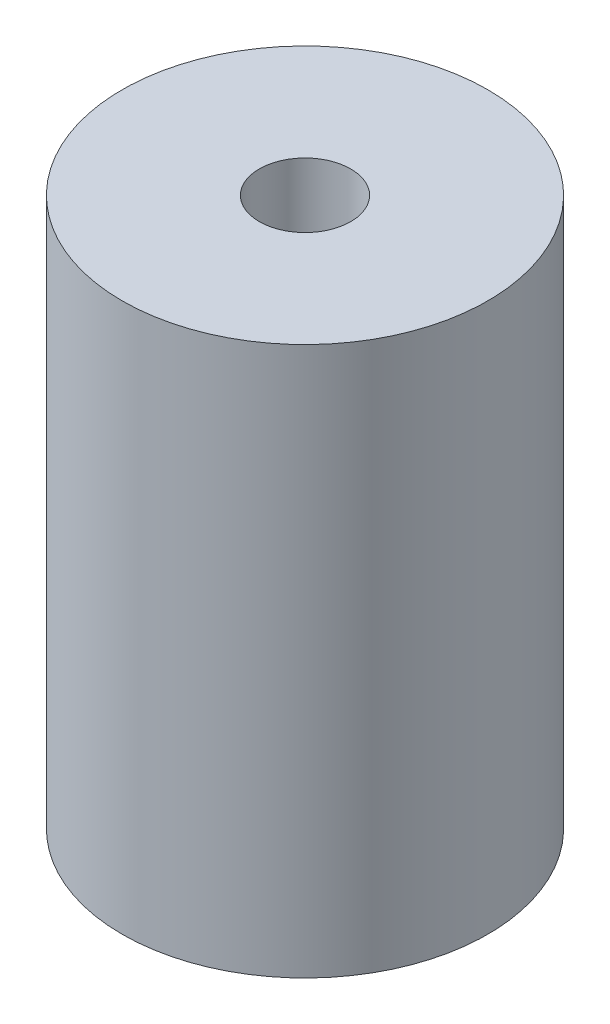
SolidWorks part; units mm, degrees
ref_plane "Front Plane" through (0, 0, 0) normal (0, 0, 1) x (1, 0, 0)
ref_plane "Top Plane" through (0, 0, 0) normal (0, 1, 0) x (1, 0, 0)
ref_plane "Right Plane" through (0, 0, 0) normal (1, 0, 0) x (0, 0, -1)
sketch "Sketch1" plane through (0, 0, 0) normal (0, 1, 0) x (1, 0, 0)
  circle A0 centre (0, 0) radius 10
  point P3 (0, 0)
  dimension "D1" = 20
extrude "Boss-Extrude1" add sketch "Sketch1" along normal blind 30
sketch "Sketch2" plane through (0, 30, 0) normal (0, 1, 0) x (1, 0, 0)
  circle A0 centre (0, 0) radius 2.5
  dimension "D1" = 5
extrude "Cut-Extrude1" cut sketch "Sketch2" against normal blind 30 contours A0
